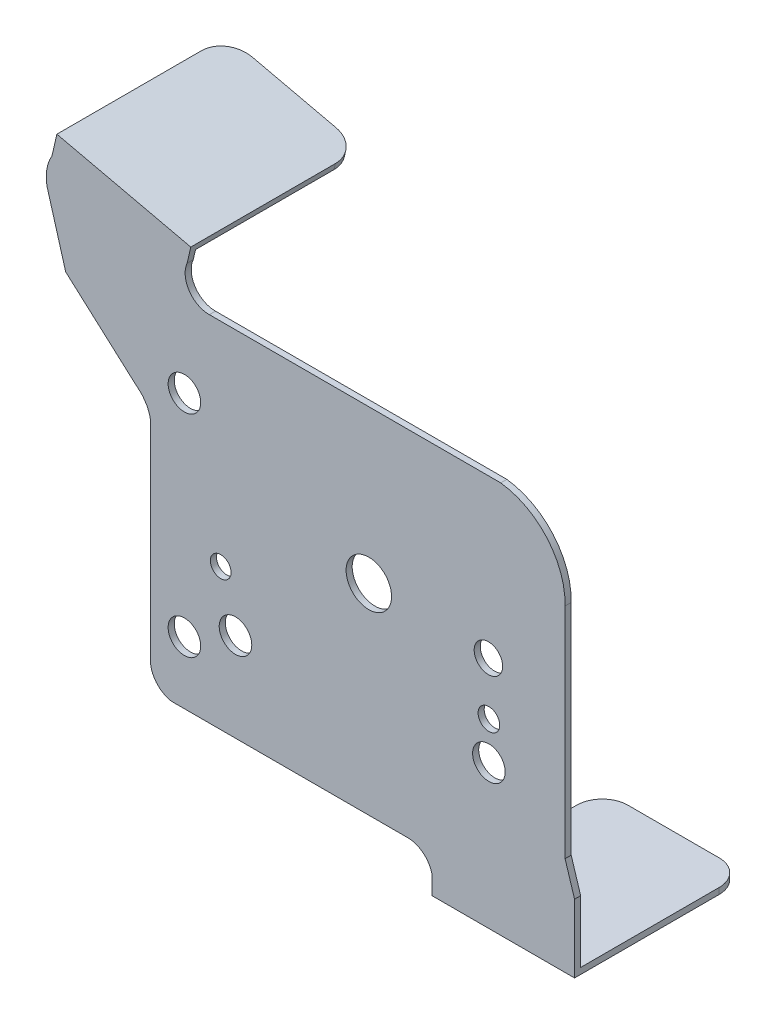
SolidWorks part; units mm, degrees
ref_plane "Alzado" through (0, 0, 0) normal (0, 0, 1) x (1, 0, 0)
ref_plane "Planta" through (0, 0, 0) normal (0, 1, 0) x (1, 0, 0)
ref_plane "Vista lateral" through (0, 0, 0) normal (1, 0, 0) x (0, 0, -1)
sketch "Croquis1" plane through (0, 0, 0) normal (0, 0, 1) x (1, 0, 0)
  line L0 (2788.5159, 1163.0629) -> (2845.3203, 1163.0629)
  line L1 (2857.8614, 1148.5546) -> (2857.8614, 1105.8847)
  line L2 (2857.8614, 1105.8847) -> (2859.7096, 1099.9695)
  line L3 (2859.7096, 1099.9695) -> (2859.7096, 1086.6685)
  line L4 (2859.7096, 1086.6685) -> (2831.925, 1086.6685)
  line L5 (2831.925, 1090.237) -> (2831.925, 1086.6685)
  line L6 (2781.0738, 1094.0948) -> (2827.4673, 1094.0948)
  line L7 (2777.0773, 1099.7185) -> (2777.0773, 1139.3578)
  line L8 (2774.3125, 1143.942) -> (2760.5085, 1156.2703)
  line L9 (2760.5085, 1156.2703) -> (2756.8696, 1168.8846)
  line L10 (2757.8278, 1174.4924) -> (2758.7888, 1178.6707)
  line L11 (2784.8931, 1172.6668) -> (2784.1913, 1169.6153)
  line L12 (2784.8931, 1172.6668) -> (2758.7888, 1178.6707)
  line L13 (2783.6509, 1147.3752) -> (2783.6509, 1106.2537) construction
  arc A0 (2857.8614, 1148.5546) -> (2845.3203, 1163.0629) centre (2843.5531, 1148.8609) ccw
  arc A5 (2831.925, 1090.237) -> (2827.4673, 1094.0948) centre (2827.128, 1089.1983) ccw
  arc A6 (2777.0773, 1099.7185) -> (2781.0738, 1094.0948) centre (2782.0012, 1098.9858) ccw
  arc A7 (2777.0773, 1139.3578) -> (2774.3125, 1143.942) centre (2770.304, 1138.3986) ccw
  arc A8 (2757.8278, 1174.4924) -> (2756.8696, 1168.8846) centre (2764.6187, 1170.4463) ccw
  arc A15 (2784.1913, 1169.6153) -> (2788.5159, 1163.0629) centre (2788.4536, 1167.7251) ccw
  circle A16 centre (2819.6018, 1133.2354) radius 4.4305
  circle A17 centre (2790.7272, 1121.6381) radius 2.0215
  circle A18 centre (2783.6509, 1147.3752) radius 3.175
  circle A19 centre (2793.6078, 1111.4193) radius 3.175
  circle A20 centre (2783.6509, 1106.2537) radius 3.175
  circle A22 centre (2842.9135, 1132.266) radius 2.7764
  circle A23 centre (2843.0093, 1122.0339) radius 2.1062
  circle A24 centre (2843.0093, 1114.6706) radius 3.175
  point P0 (2777.0773, 1119.5381)
  point P1 (0, 0)
  dimension "D1" = 41.1215
  dimension "D3" = 12.1589
  dimension "D4" = 6.35
  dimension "D6" = 6.35
  dimension "D2" = 6.5737
  dimension "D5" = 14.8521
extrude "Saliente-Extruir1" add sketch "Croquis1" along normal blind 1.19
sketch "Croquis4" plane through (0, 0, 1.19) normal (0, 0, 1) x (1, 0, 0)
  line L0 (2859.7096, 1086.6685) -> (2859.7096, 1099.9695) construction
  line L1 (2831.925, 1086.6685) -> (2859.7096, 1086.6685)
  line L2 (2831.925, 1086.6685) -> (2831.925, 1087.8585)
  line L3 (2831.925, 1087.8585) -> (2859.7096, 1087.8585)
  line L4 (2859.7096, 1086.6685) -> (2859.7096, 1087.8585)
  line L5 (2784.8931, 1172.6668) -> (2784.6264, 1171.507)
  line L6 (2784.1913, 1169.6153) -> (2784.8931, 1172.6668) construction
  line L7 (2784.6264, 1171.507) -> (2758.522, 1177.511)
  line L9 (2758.522, 1177.511) -> (2758.7888, 1178.6707)
  line L10 (2758.7888, 1178.6707) -> (2784.8931, 1172.6668)
  dimension "D1" = 1.19
  dimension "D2" = 1.19
extrude "Saliente-Extruir2" add sketch "Croquis4" against normal blind 33.19
fillet "Redondeo2" radius 5 4 edges at (2784.7598, 1172.0869, -32) (2758.6554, 1178.0908, -32) (2831.925, 1087.2635, -32) (2859.7096, 1087.2635, -32)
